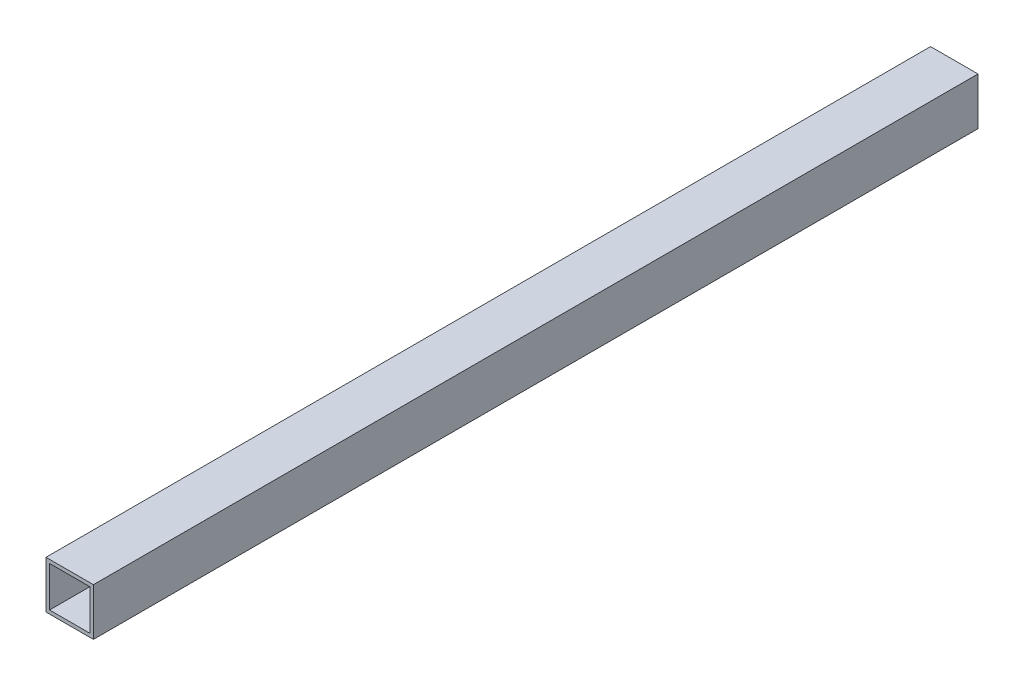
SolidWorks part; units mm, degrees
material "6063-T6"
ref_plane "Płaszczyzna przednia" through (0, 0, 0) normal (0, 0, 1) x (1, 0, 0)
ref_plane "Płaszczyzna górna" through (0, 0, 0) normal (0, 1, 0) x (1, 0, 0)
ref_plane "Płaszczyzna prawa" through (0, 0, 0) normal (1, 0, 0) x (0, 0, -1)
sketch "Szkic1" plane through (0, 0, 0) normal (0, 0, 1) x (1, 0, 0)
  line L0 (8.5, 8.5) -> (-8.5, 8.5)
  line L1 (10, -10) -> (-10, -10)
  line L2 (10, -10) -> (10, 10)
  line L3 (10, 10) -> (-10, 10)
  line L4 (-10, -10) -> (-10, 10)
  line L5 (10, -10) -> (-10, 10) construction
  line L6 (10, 10) -> (-10, -10) construction
  line L7 (-8.5, -8.5) -> (-8.5, 8.5)
  line L8 (8.5, -8.5) -> (-8.5, -8.5)
  line L9 (8.5, -8.5) -> (8.5, 8.5)
  point P0 (0, 0)
  dimension "D1" = 20
  dimension "D2" = 20
  dimension "D3" = 1.5
extrude "Dodanie-wyciągnięcie1" add sketch "Szkic1" along normal blind 373
